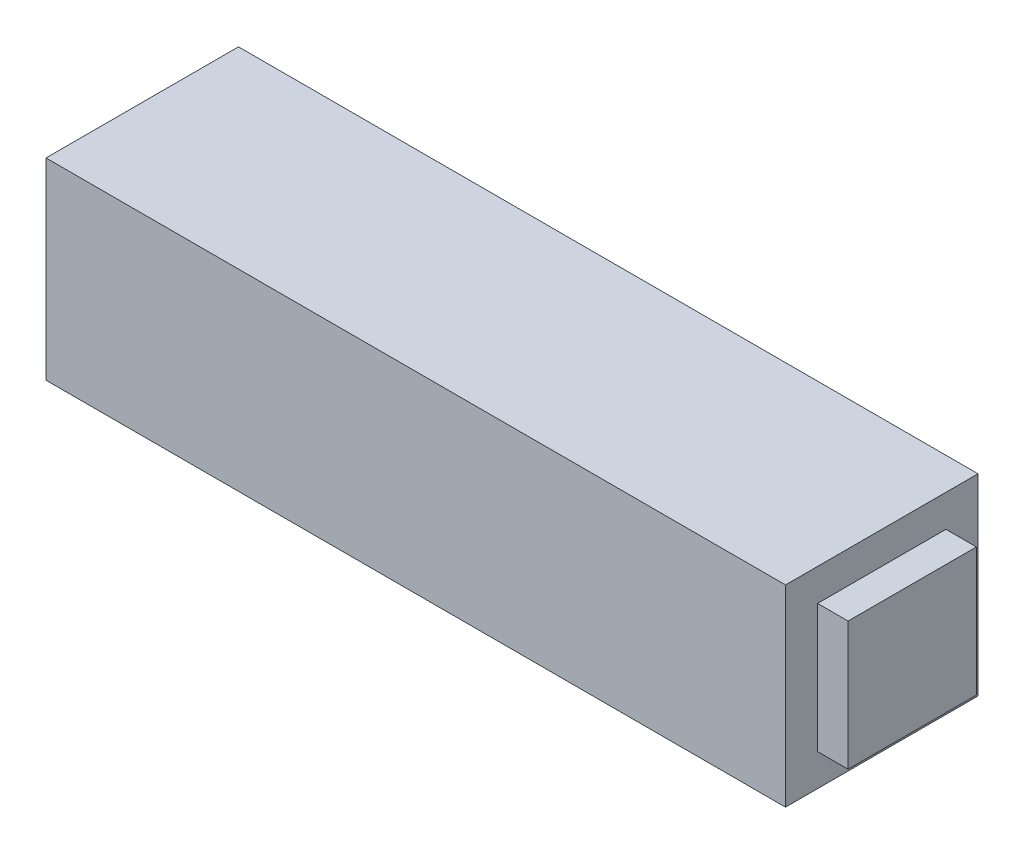
SolidWorks part; units mm, degrees
ref_plane "Front Plane" through (0, 0, 0) normal (0, 0, 1) x (1, 0, 0)
ref_plane "Top Plane" through (0, 0, 0) normal (0, 1, 0) x (1, 0, 0)
ref_plane "Right Plane" through (0, 0, 0) normal (1, 0, 0) x (0, 0, -1)
sketch "Sketch1" plane through (0, 0, 0) normal (0, 0, 1) x (1, 0, 0)
  line L1 (-57.625, -18.0776) -> (57.625, -18.0776)
  line L2 (-57.625, -18.0776) -> (-57.625, 11.9224)
  line L3 (-57.625, 11.9224) -> (57.625, 11.9224)
  line L4 (57.625, -18.0776) -> (57.625, 11.9224)
  dimension "D1" = 115.25
  dimension "D2" = 30
extrude "Boss-Extrude1" add sketch "Sketch1" along normal mid plane 30
sketch "Sketch2" plane through (-57.625, 0, 0) normal (-1, 0, 0) x (0, 0, 1)
  line L0 (15, 11.9224) -> (-15, 11.9224) construction
  line L1 (-10.25, -13.5776) -> (10.25, -13.5776)
  line L2 (-10.25, -13.5776) -> (-10.25, 6.9224)
  line L3 (-10.25, 6.9224) -> (10.25, 6.9224)
  line L4 (10.25, -13.5776) -> (10.25, 6.9224)
  dimension "D1" = 5
extrude "Cut-Extrude2" cut sketch "Sketch2" against normal blind 10
sketch "Sketch3" plane through (57.625, 0, 0) normal (1, 0, 0) x (0, 0, -1)
  line L0 (-15, 11.9224) -> (15, 11.9224) construction
  line L1 (-10, -13.0776) -> (10, -13.0776)
  line L2 (-10, -13.0776) -> (-10, 6.9224)
  line L3 (-10, 6.9224) -> (10, 6.9224)
  line L4 (10, -13.0776) -> (10, 6.9224)
  line L5 (-15, -18.0776) -> (-15, 11.9224) construction
  dimension "D1" = 5
  dimension "D2" = 5
extrude "Boss-Extrude2" add sketch "Sketch3" along normal blind 4.75
